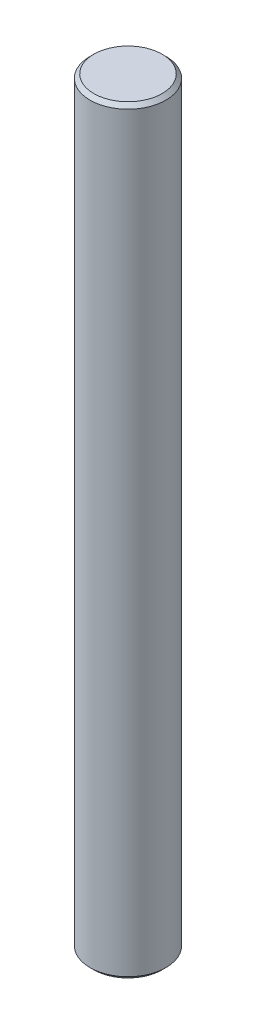
SolidWorks part; units mm, degrees
material "Chromowa stal nierdzewna"
ref_plane "Płaszczyzna przednia" through (0, 0, 0) normal (0, 0, 1) x (1, 0, 0)
ref_plane "Płaszczyzna górna" through (0, 0, 0) normal (0, 1, 0) x (1, 0, 0)
ref_plane "Płaszczyzna prawa" through (0, 0, 0) normal (1, 0, 0) x (0, 0, -1)
sketch "Szkic1" plane through (0, 0, 0) normal (0, 1, 0) x (1, 0, 0)
  circle A0 centre (0, 0) radius 2.5
  dimension "D1" = 5
extrude "Dodanie-wyciągnięcie1" add sketch "Szkic1" along normal blind 50
chamfer "Sfazowanie1" distance 0.25 angle 45 2 edges at (0, 0, 2.5) (0, 50, 2.5)
